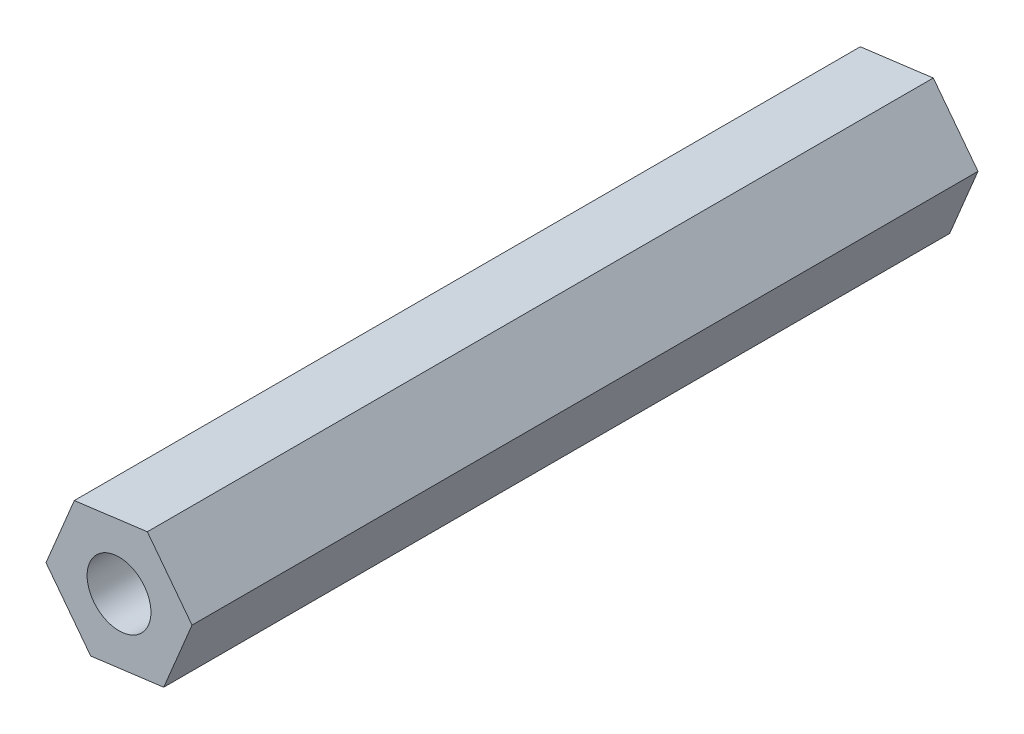
SolidWorks part; units mm, degrees
ref_plane "Front Plane" through (0, 0, 0) normal (0, 0, 1) x (1, 0, 0)
ref_plane "Top Plane" through (0, 0, 0) normal (0, 1, 0) x (1, 0, 0)
ref_plane "Right Plane" through (0, 0, 0) normal (1, 0, 0) x (0, 0, -1)
sketch "Sketch1" plane through (0, 0, 0) normal (0, 0, 1) x (1, 0, 0)
  line L1 (7.2715, 0.9426) -> (2.8194, 6.7686)
  line L2 (2.8194, 6.7686) -> (-4.4521, 5.826)
  line L3 (-4.4521, 5.826) -> (-7.2715, -0.9426)
  line L4 (-7.2715, -0.9426) -> (-2.8194, -6.7686)
  line L5 (-2.8194, -6.7686) -> (4.4521, -5.826)
  line L6 (4.4521, -5.826) -> (7.2715, 0.9426)
  circle A0 centre (0, 0) radius 6.35 construction
  circle A1 centre (0, 0) radius 3.18
extrude "Boss-Extrude1" add sketch "Sketch1" along normal blind 78.27
move or copy body "Body-Move/Copy1" [suppressed] bodies to move or copy 101
